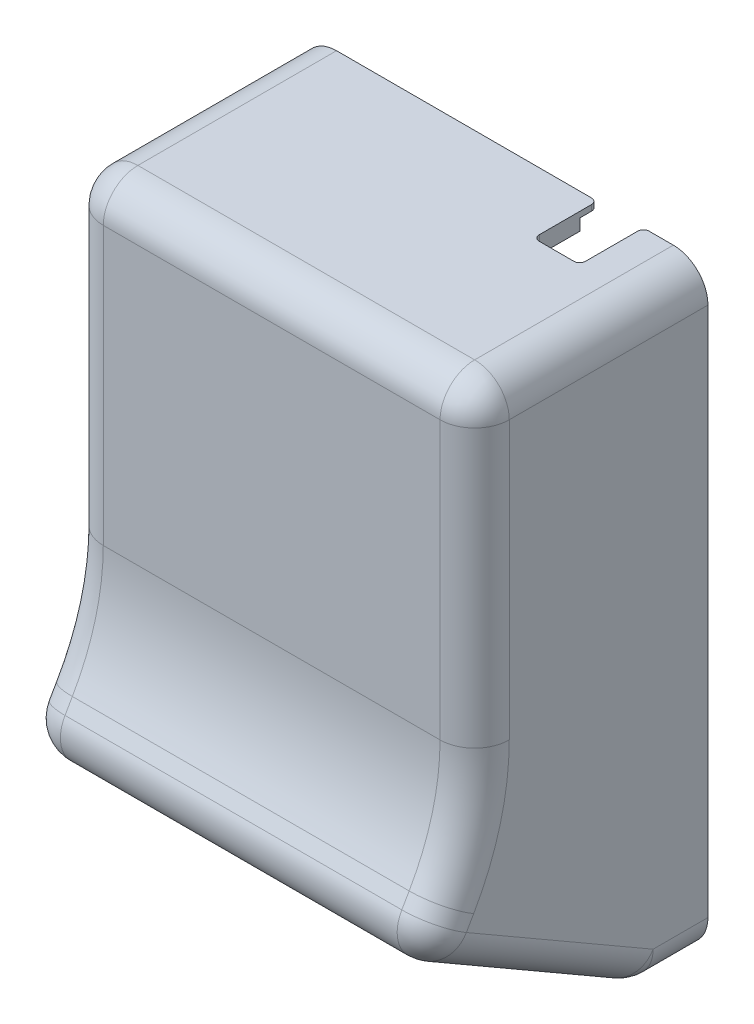
SolidWorks part; units mm, degrees
ref_plane "Front Plane" through (0, 0, 0) normal (0, 0, 1) x (1, 0, 0)
ref_plane "Top Plane" through (0, 0, 0) normal (0, 1, 0) x (1, 0, 0)
ref_plane "Right Plane" through (0, 0, 0) normal (1, 0, 0) x (0, 0, -1)
sketch "Sketch1" plane through (0, -25.2518, 14.5792) normal (0, -0.866, 0.5) x (1, 0, 0)
  line L0 (1.2346, 10.2153) -> (1.2346, 1.2153) construction
  line L1 (-0.0154, 1.2153) -> (2.4846, 1.2153)
  line L2 (-0.0154, 1.2153) -> (-0.0154, 6.6268)
  line L3 (2.4846, 1.2153) -> (2.4846, 6.6268)
  line L5 (-14.8654, 20.7153) -> (17.3346, 20.7153)
  line L6 (-14.8654, 20.7153) -> (-14.8654, -0.2847)
  line L7 (-14.8654, -0.2847) -> (17.3346, -0.2847)
  line L8 (17.3346, 20.7153) -> (17.3346, -0.2847)
  line L9 (-14.8654, 20.7153) -> (17.3346, -0.2847) construction
  line L10 (-14.8654, -0.2847) -> (17.3346, 20.7153) construction
  arc A0 (2.4846, 6.6268) -> (-0.0154, 6.6268) centre (1.2346, 10.2153) ccw
  point P7 (1.2346, 1.2153)
  dimension "D1" = 7.6
  dimension "D2" = 9
  dimension "D3" = 1.25
  dimension "D4" = 21
  dimension "D5" = 32.2
extrude "Boss-Extrude2" add sketch "Sketch1" along normal blind 1.5
sketch "Sketch2" plane through (17.3346, 0, 0) normal (1, 0, 0) x (0, 0, -1)
  line L0 (-15.0826, -26.6932) -> (-9.5257, -26.6932)
  line L1 (-9.5257, -26.6932) -> (-9.5257, 25.2956)
  line L2 (-9.5257, 25.2956) -> (-28.2519, 25.2956)
  line L3 (-28.2519, 25.2956) -> (-28.2519, -7.5031)
  line L5 (-33.2691, -16.1932) -> (-15.0826, -26.6932)
  line L6 (-33.2691, -16.1932) -> (-28.2519, -7.5031)
  point P3 (-28.2519, 0)
  point P9 (-28.2519, -7.0412)
extrude "Boss-Extrude3" add sketch "Sketch2" along normal blind 1.5
sketch "Sketch3" plane through (-14.8654, 0, 0) normal (-1, 0, 0) x (0, 0, 1)
  line L0 (28.2519, 25.2956) -> (28.2519, -7.5031)
  line L1 (28.2519, 25.2956) -> (28.2519, -7.5031)
  line L2 (28.2519, -7.5031) -> (33.2691, -16.1932)
  line L3 (28.2519, -7.5031) -> (33.2691, -16.1932)
  line L4 (33.2691, -16.1932) -> (15.0826, -26.6932)
  line L5 (33.2691, -16.1932) -> (15.0826, -26.6932)
  line L6 (15.0826, -26.6932) -> (9.5257, -26.6932)
  line L7 (15.0826, -26.6932) -> (9.5257, -26.6932)
  line L8 (9.5257, -26.6932) -> (9.5257, 25.2956)
  line L9 (9.5257, -26.6932) -> (9.5257, 25.2956)
  line L10 (9.5257, 25.2956) -> (28.2519, 25.2956)
  line L11 (9.5257, 25.2956) -> (28.2519, 25.2956)
extrude "Boss-Extrude4" add sketch "Sketch3" along normal blind 1.5
sketch "Sketch4" plane through (18.8346, 0, 0) normal (1, 0, 0) x (0, 0, -1)
  line L0 (-28.2519, -7.5031) -> (-33.2691, -16.1932) construction
  line L1 (-28.2519, 25.2956) -> (-28.2519, -7.5031) construction
  line L2 (-28.2519, -7.5031) -> (-33.2691, -16.1932)
  line L3 (-28.2519, 25.2956) -> (-28.2519, -7.5031)
  line L4 (-29.7519, 25.2956) -> (-29.7519, -7.1011)
  line L5 (-29.7519, -7.1011) -> (-34.5682, -15.4432)
  line L6 (-33.2691, -16.1932) -> (-34.5682, -15.4432)
  line L7 (-29.7519, 25.2956) -> (-28.2519, 25.2956)
  dimension "D1" = 1.5
extrude "Boss-Extrude5" add sketch "Sketch4" against normal up to surface (35.2 mm away) up to face at (-16.3654, -4.4153, 20.6512)
sketch "Sketch5" plane through (0, -26.6932, 0) normal (0, -1, 0) x (1, 0, 0)
  line L1 (-16.3654, 15.0826) -> (18.8346, 15.0826)
  line L2 (-16.3654, 15.0826) -> (-16.3654, 9.5257)
  line L3 (-16.3654, 9.5257) -> (18.8346, 9.5257)
  line L4 (18.8346, 15.0826) -> (18.8346, 9.5257)
extrude "Boss-Extrude6" add sketch "Sketch5" against normal blind 1.5
sketch "Sketch6" plane through (0, 25.2956, 0) normal (0, 1, 0) x (1, 0, 0)
  line L1 (-16.3654, -9.5257) -> (18.8346, -9.5257)
  line L2 (-16.3654, -9.5257) -> (-16.3654, -29.7519)
  line L3 (-16.3654, -29.7519) -> (18.8346, -29.7519)
  line L4 (18.8346, -9.5257) -> (18.8346, -29.7519)
extrude "Boss-Extrude7" add sketch "Sketch6" against normal blind 1.5
fillet "Fillet3" radius 20 1 edges at (1.2346, -7.1011, 29.7519)
fillet "Fillet-Exterior" radius 3 15 edges at (1.2346, 25.2956, 29.7519) (-16.3654, 25.2956, 19.6388) (-16.3654, 11.7767, 29.7519) (18.8346, 11.7767, 29.7519) (18.8346, -13.5927, 33.4998) (-16.3654, -13.5927, 33.4998) (-16.3654, -21.0682, 24.8254) (-16.3654, -26.6932, 12.3042) (18.8346, 25.2956, 19.6388) (18.8346, -26.6932, 12.3042) (18.8346, -21.0682, 24.8254) (1.2346, -15.4432, 34.5682) (1.2346, -26.6932, 15.0826) (-16.3654, -6.9185, 30.4334) (18.8346, -6.9185, 30.4334)
fillet "Fillet-Interior" radius 1.5 14 edges at (-14.8654, -11.1986, 30.3855) (17.3346, -11.1986, 30.3855) (1.2346, -7.5031, 28.2519) (17.3346, 8.1463, 28.2519) (1.2346, 23.7956, 28.2519) (-14.8654, 8.1463, 28.2519) (1.2346, -14.8942, 32.5191) (17.3346, 23.7956, 18.8888) (-14.8654, 23.7956, 18.8888) (17.3346, -20.0437, 23.5999) (1.2346, -25.1932, 14.6807) (-14.8654, -20.0437, 23.5999) (17.3346, -25.1932, 12.1032) (-14.8654, -25.1932, 12.1032)
sketch "Sketch7" plane through (0, 25.2956, 0) normal (0, 1, 0) x (1, 0, 0)
  line L2 (12.7096, -10.59) -> (12.7096, -8.5) construction
  line L3 (12.7096, -8.5) -> (12.5225, -8.5) construction
  line L4 (9.9567, -13.8) -> (9.9567, -7.8) construction
  line L5 (9.9567, -7.8) -> (9.7696, -7.8) construction
  line L6 (9.7696, -7.8) -> (9.7696, -13.8) construction
  line L7 (9.7696, -13.8) -> (9.9567, -13.8) construction
  line L10 (12.7096, -14.3098) -> (12.7096, -8.5) construction
  line L11 (12.7096, -8.5) -> (12.5225, -8.5) construction
  line L12 (9.9567, -13.8) -> (9.9567, -7.8) construction
  line L13 (9.9567, -7.8) -> (9.7696, -7.8) construction
  line L14 (9.7696, -7.8) -> (9.7696, -13.8) construction
  line L15 (9.7696, -13.8) -> (9.9567, -13.8) construction
  line L16 (9.7696, -10.8) -> (12.7096, -10.8) construction
  line L17 (11.2396, -15.05) -> (11.2396, -6.55) construction
  line L18 (13.2396, -15.05) -> (13.2396, -6.55)
  line L19 (9.2396, -15.05) -> (9.2396, -6.55)
  line L20 (9.2396, -6.55) -> (13.2396, -6.55)
  line L21 (9.2396, -15.05) -> (13.2396, -15.05)
  point P10 (11.2396, -10.59)
  point P14 (11.2396, -10.8)
  dimension "D1" = 8.5
  dimension "D2" = 2
  dimension "D3" = 2
extrude "Cut-Extrude1" cut sketch "Sketch7" against normal blind 1.5
fillet "Fillet4" radius 0.5 4 edges at (9.2396, 24.5456, 15.05) (9.2396, 24.5456, 9.5257) (13.2396, 24.5456, 9.5257) (13.2396, 24.5456, 15.05)
sketch "Sketch9" plane through (0, 0, 9.5257) normal (0, 0, -1) x (-1, 0, 0)
  line L8 (14.8654, 22.2956) -> (14.8654, -23.6932) construction
  line L10 (-17.3346, -23.6932) -> (-17.3346, 22.2956) construction
  line L18 (14.8654, 22.2956) -> (14.8654, -23.6932)
  line L20 (-17.3346, -23.6932) -> (-17.3346, 22.2956)
  line L21 (-15.8346, 23.7956) -> (13.3654, 23.7956)
  line L22 (13.3654, -24.9923) -> (-15.8346, -24.9923)
  line L23 (13.3654, -25.9923) -> (-15.8346, -25.9923)
  line L24 (-18.3346, -23.6932) -> (-18.3346, 22.2956)
  line L25 (-15.8346, 24.7956) -> (13.3654, 24.7956)
  line L26 (15.8654, 22.2956) -> (15.8654, -23.6932)
  arc A8 (14.8654, 22.2956) -> (13.3654, 23.7956) centre (13.3654, 22.2956) ccw construction
  arc A9 (-15.8346, 23.7956) -> (-17.3346, 22.2956) centre (-15.8346, 22.2956) ccw construction
  arc A10 (14.8654, 22.2956) -> (13.3654, 23.7956) centre (13.3654, 22.2956) ccw
  arc A11 (-15.8346, 23.7956) -> (-17.3346, 22.2956) centre (-15.8346, 22.2956) ccw
  arc A12 (-15.8346, 24.7956) -> (-18.3346, 22.2956) centre (-15.8346, 22.2956) ccw
  arc A13 (15.8654, 22.2956) -> (13.3654, 24.7956) centre (13.3654, 22.2956) ccw
  ellipse E0 centre (-15.8346, -23.6932) end of major axis (-17.3346, -23.6932) minor radius 1.299 (-17.3346, -23.6932) -> (-15.8346, -24.9923) ccw construction
  ellipse E1 centre (13.3654, -23.6932) end of major axis (11.8654, -23.6932) minor radius 1.299 (13.3654, -24.9923) -> (14.8654, -23.6932) ccw construction
  ellipse E2 centre (-15.8346, -23.6932) end of major axis (-17.3346, -23.6932) minor radius 1.299 (-17.3346, -23.6932) -> (-15.8346, -24.9923) ccw
  ellipse E3 centre (13.3654, -23.6932) end of major axis (11.8654, -23.6932) minor radius 1.299 (13.3654, -24.9923) -> (14.8654, -23.6932) ccw
  spline S0 degree 1 poles (-18.3346, -23.6932) (-15.8346, -25.9923) knots 0 0 1 1 construction
  spline S1 degree 1 poles (13.3654, -25.9923) (15.8654, -23.6932) knots 0 0 1 1 construction
  spline S2 degree 3 poles (-15.8346, -25.9923) (-16.143, -25.9923) (-16.7644, -25.8868) (-17.5876, -25.4156) (-18.1845, -24.6569) (-18.3346, -24.0107) (-18.3346, -23.6932) knots 0 0 0 0 0.392699 0.785398 1.178097 1.570796 1.570796 1.570796 1.570796
  spline S3 degree 3 poles (15.8654, -23.6932) (15.8654, -24.0107) (15.7153, -24.6569) (15.1185, -25.4156) (14.2953, -25.8868) (13.6738, -25.9923) (13.3654, -25.9923) knots 1.570796 1.570796 1.570796 1.570796 1.963495 2.356194 2.748894 3.141593 3.141593 3.141593 3.141593
  dimension "D1" = 1
extrude "Cut-Extrude2" cut sketch "Sketch9" against normal blind 1.5
sketch "Sketch10" plane through (0, 0, 11.0257) normal (0, 0, -1) x (-1, 0, 0)
  circle A0 centre (13.3654, 22.2956) radius 0.8
  circle A2 centre (13.3654, 22.2956) radius 2.3
  dimension "D1" = 1.6
  dimension "D2" = 1.5
extrude "Screw-Boss1" add sketch "Sketch10" against normal up to surface (17.2261 mm away) up to face at (1.2346, 7.5972, 28.2519)
sketch "Sketch11" plane through (0, 0, 11.0257) normal (0, 0, -1) x (-1, 0, 0)
  circle A0 centre (13.3654, -23.6932) radius 0.8
  circle A1 centre (13.3654, -23.6932) radius 2.3
  dimension "D1" = 1.6
  dimension "D2" = 1.5
extrude "Screw-Boss2" add sketch "Sketch11" against normal up to surface (6.253 mm away)
equation "\"D5@Sketch1\"=35.00mm-2.8"
